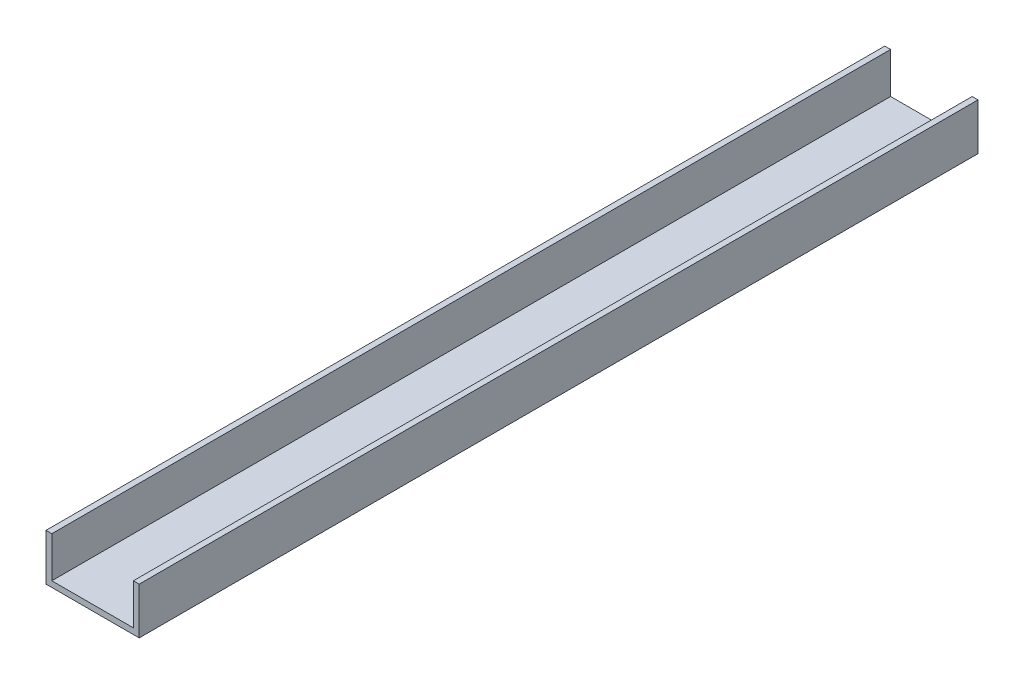
SolidWorks part; units mm, degrees
ref_plane "Front Plane" through (0, 0, 0) normal (0, 0, 1) x (1, 0, 0)
ref_plane "Top Plane" through (0, 0, 0) normal (0, 1, 0) x (1, 0, 0)
ref_plane "Right Plane" through (0, 0, 0) normal (1, 0, 0) x (0, 0, -1)
sketch "Sketch1" plane through (0, 0, 0) normal (0, 0, 1) x (1, 0, 0)
  line L0 (3.175, 3.175) -> (3.175, 25.4)
  line L1 (0, 0) -> (50.8, 0)
  line L2 (0, 0) -> (0, 25.4)
  line L3 (0, 25.4) -> (3.175, 25.4)
  line L4 (50.8, 0) -> (50.8, 25.4)
  line L5 (0, 0) -> (50.8, 25.4) construction
  line L6 (0, 25.4) -> (50.8, 0) construction
  line L7 (3.175, 3.175) -> (3.175, 22.225) construction
  line L8 (47.625, 3.175) -> (47.625, 25.4)
  line L9 (3.175, 3.175) -> (47.625, 3.175)
  line L10 (3.175, 22.225) -> (47.625, 22.225) construction
  line L11 (47.625, 3.175) -> (47.625, 22.225) construction
  line L12 (47.625, 25.4) -> (50.8, 25.4)
  line L13 (0, 25.4) -> (50.8, 25.4) construction
  point P4 (25.4, 12.7)
  dimension "D1" = 25.4
  dimension "D2" = 50.8
  dimension "D3" = 3.175
extrude "Boss-Extrude1" add sketch "Sketch1" along normal blind 457.2
sketch "Sketch2" plane through (0, 3.175, 0) normal (0, 1, 0) x (1, 0, 0)
  circle A1 centre (12.3849, -132.8188) radius 3.175
extrude "Cut-Extrude1" [suppressed] cut sketch "Sketch2" against normal up to next
